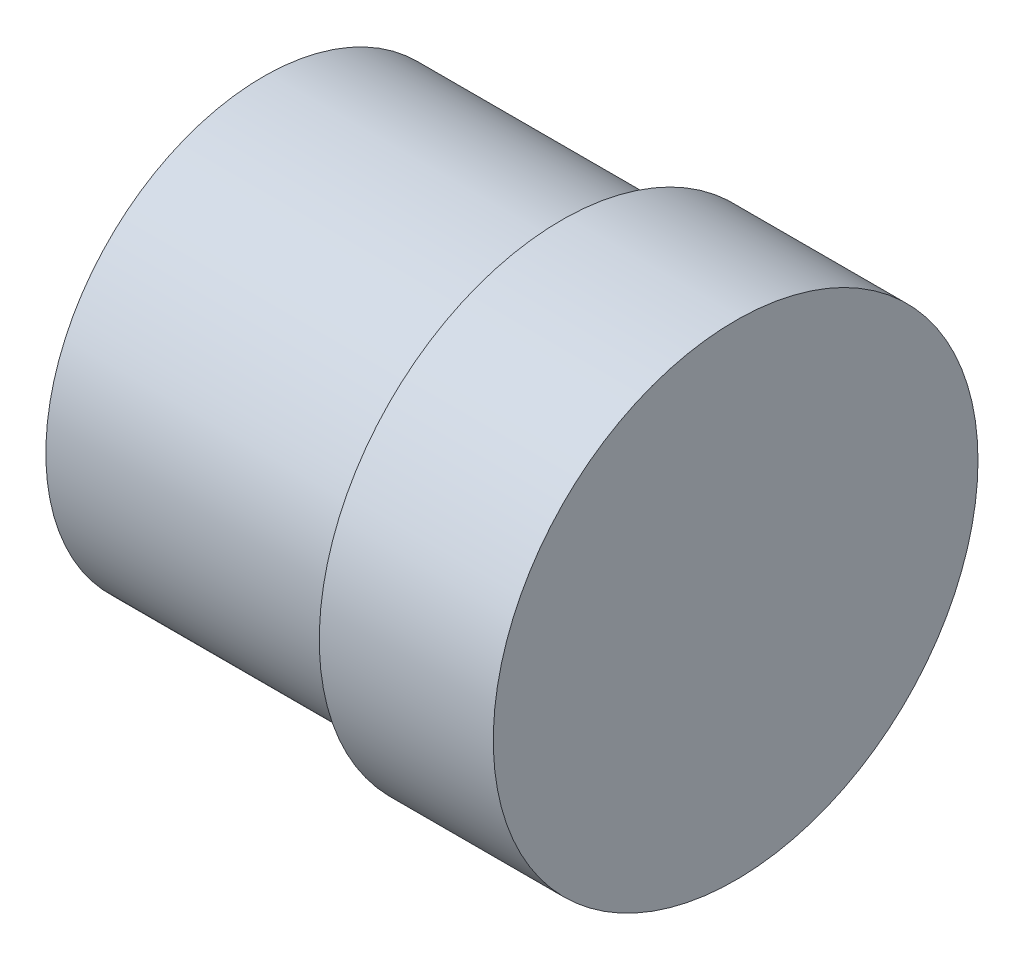
SolidWorks part; units mm, degrees
ref_plane "Front Plane" through (0, 0, 0) normal (0, 0, 1) x (1, 0, 0)
ref_plane "Top Plane" through (0, 0, 0) normal (0, 1, 0) x (1, 0, 0)
ref_plane "Right Plane" through (0, 0, 0) normal (1, 0, 0) x (0, 0, -1)
sketch "Sketch1" plane through (0, 0, 0) normal (1, 0, 0) x (0, 0, -1)
  circle A0 centre (0, 0) radius 495.3
  dimension "D1" = 990.6
extrude "Boss-Extrude1" add sketch "Sketch1" along normal blind 355.6
sketch "Sketch2" plane through (0, 0, 0) normal (1, 0, 0) x (0, 0, -1)
  circle A0 centre (0, 0) radius 444.5
  dimension "D1" = 889
extrude "Boss-Extrude3" add sketch "Sketch2" against normal blind 609.6
sketch "Sketch3" plane through (0, 0, 0) normal (1, 0, 0) x (0, 0, -1)
  line L0 (0, 0) -> (-668.422, 0) construction
